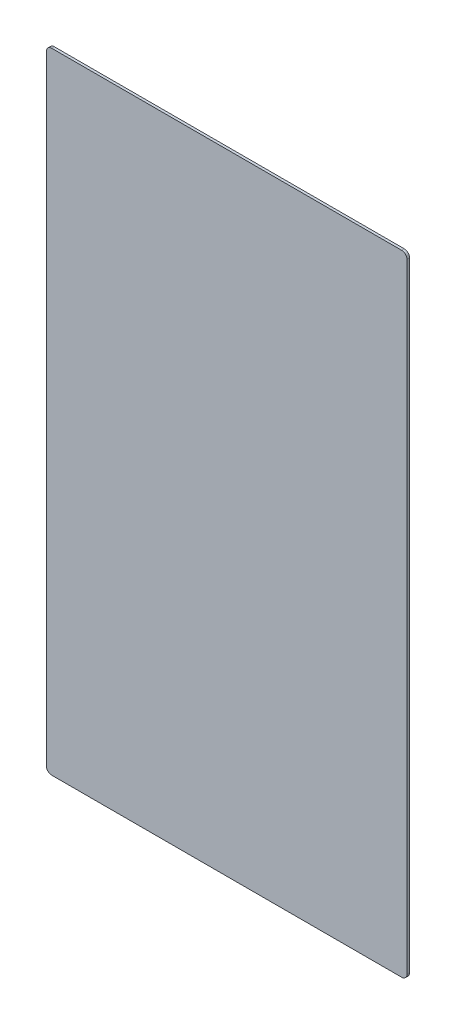
SolidWorks part; units mm, degrees
ref_plane "前视基准面" through (0, 0, 0) normal (0, 0, 1) x (1, 0, 0)
ref_plane "上视基准面" through (0, 0, 0) normal (0, 1, 0) x (1, 0, 0)
ref_plane "右视基准面" through (0, 0, 0) normal (1, 0, 0) x (0, 0, -1)
sketch "草图1" plane through (0, 0, 0) normal (0, 0, 1) x (1, 0, 0)
  line L1 (-345, -602.5) -> (345, -602.5)
  line L2 (-345, -602.5) -> (-345, 602.5)
  line L3 (-345, 602.5) -> (345, 602.5)
  line L4 (345, -602.5) -> (345, 602.5)
  line L5 (-345, -602.5) -> (345, 602.5) construction
  line L6 (-345, 602.5) -> (345, -602.5) construction
  point P0 (0, 0)
  dimension "D1" = 1205
  dimension "D2" = 690
extrude "凸台-拉伸1" add sketch "草图1" along normal blind 5
fillet "圆角1" radius 10 4 edges at (-345, 602.5, 2.5) (-345, -602.5, 2.5) (345, -602.5, 2.5) (345, 602.5, 2.5)
